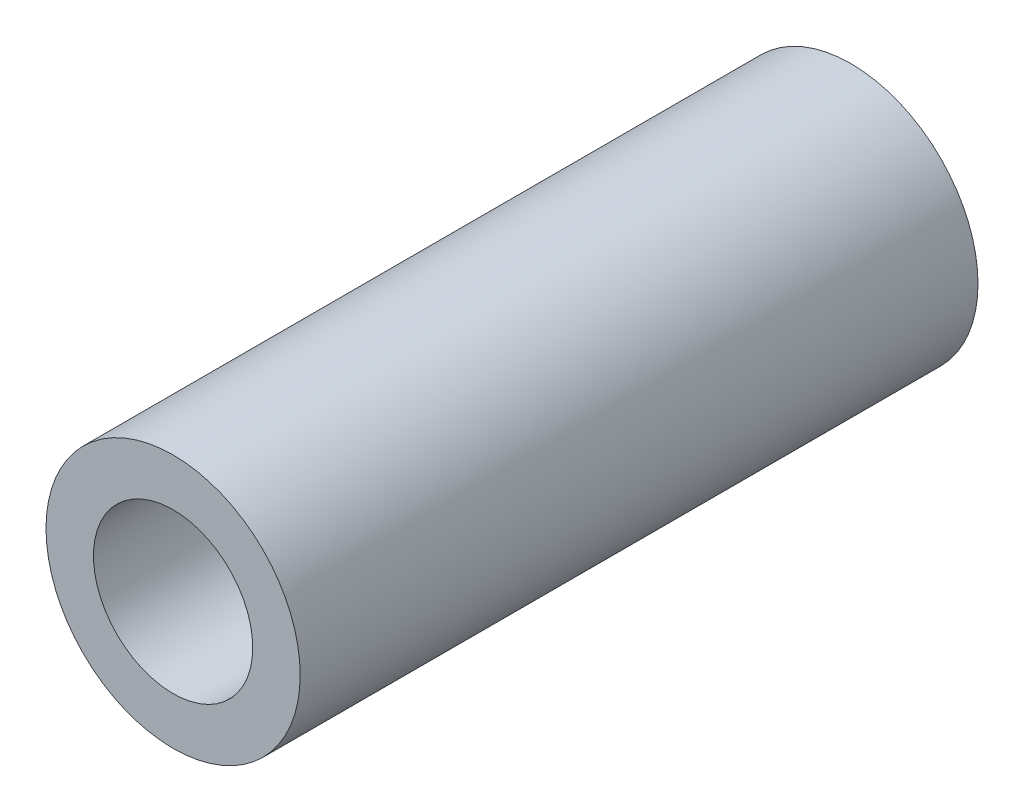
SolidWorks part; units mm, degrees
material "6061 Alloy"
ref_plane "Front Plane" through (0, 0, 0) normal (0, 0, 1) x (1, 0, 0)
ref_plane "Top Plane" through (0, 0, 0) normal (0, 1, 0) x (1, 0, 0)
ref_plane "Right Plane" through (0, 0, 0) normal (1, 0, 0) x (0, 0, -1)
sketch "Sketch1" plane through (0, 0, 0) normal (0, 0, 1) x (1, 0, 0)
  circle A0 centre (0, 0) radius 4.7625
  circle A1 centre (0, 0) radius 2.9845
  dimension "D1" = 9.525
  dimension "D2" = 5.969
extrude "Boss-Extrude1" add sketch "Sketch1" along normal blind 25.4
